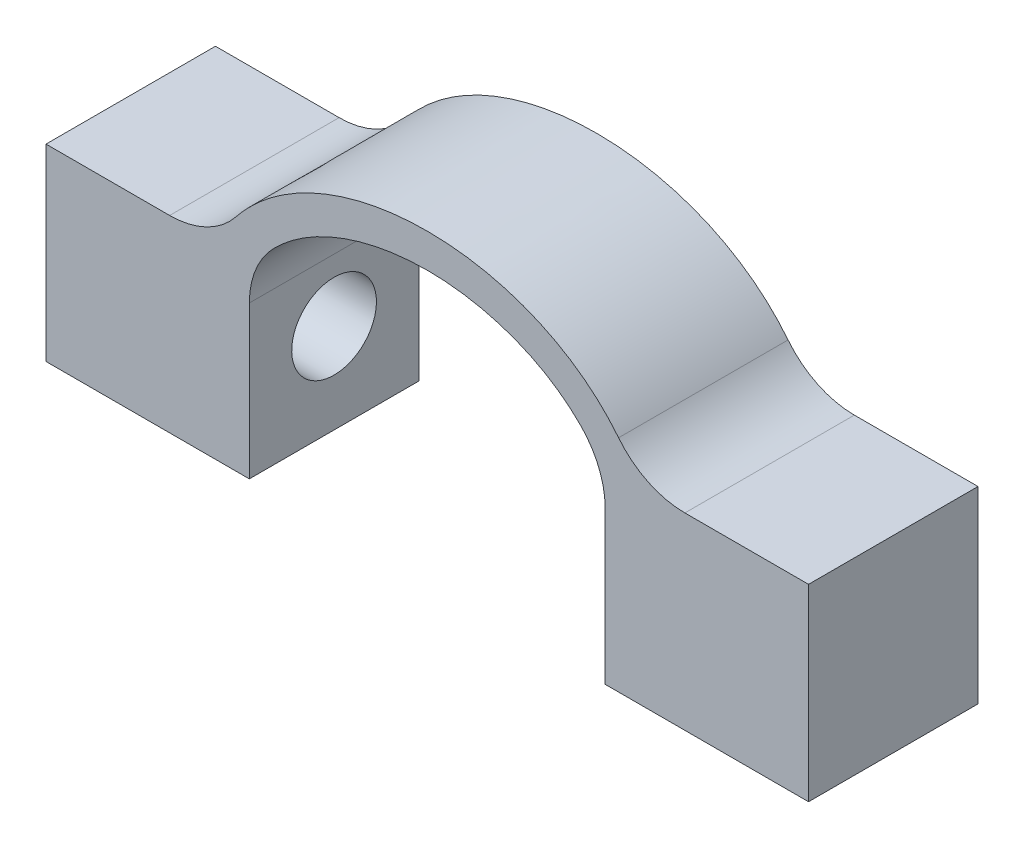
SolidWorks part; units mm, degrees
ref_plane "Front Plane" through (0, 0, 0) normal (0, 0, 1) x (1, 0, 0)
ref_plane "Top Plane" through (0, 0, 0) normal (0, 1, 0) x (1, 0, 0)
ref_plane "Right Plane" through (0, 0, 0) normal (1, 0, 0) x (0, 0, -1)
sketch "Sketch1" plane through (0, 0, 0) normal (0, 0, 1) x (1, 0, 0)
  line L4 (0, 0) -> (45, 0)
  line L5 (0, 0) -> (0, 11.1125)
  line L6 (0, 11.1125) -> (45, 11.1125) construction
  line L9 (15, 16.1125) -> (15, 11.1125) construction
  line L10 (30, 16.1125) -> (30, 11.1125) construction
  line L11 (0, 11.1125) -> (10, 11.1125)
  line L12 (35, 11.1125) -> (45, 11.1125)
  line L13 (45, 11.1125) -> (45, 0)
  spline S0 degree 3 poles (10, 11.1125) (14.5766, 20.182) (30.4234, 20.182) (35, 11.1125) knots 0 0 0 0 1 1 1 1
  dimension "D5" = 5
  dimension "D1" = 10
  dimension "D2" = 10
  dimension "D3" = 25
  dimension "D4" = 11.1125
  dimension "D6" = 5
  dimension "D7" = 5
extrude "Boss-Extrude1" add sketch "Sketch1" against normal blind 10
sketch "Sketch2" plane through (0, 0, 0) normal (0, 0, 1) x (1, 0, 0)
  line L0 (0, 0) -> (45, 0) construction
  line L2 (10, 11.1125) -> (10, 0) construction
  line L3 (10, 0) -> (35, 0) construction
  line L4 (35, 11.1125) -> (35, 0) construction
  line L5 (33, 10.6109) -> (33, 0)
  line L6 (12, 10.6109) -> (12, 0)
  spline S0 degree 3 poles (-1884.251, -531.3416) (2112.7694, 200.999) (-2067.7633, 201) (1929.2342, -531.3385) knots -3.992988 -3.992988 -3.992988 -3.992988 4.992976 4.992976 4.992976 4.992976 only from (35, 11.1125) to (10, 11.1125) construction
  spline S1 degree 3 poles (35, 11.1125) (30.4234, 20.182) (14.5766, 20.182) (10, 11.1125) knots 0 0 0 0 1 1 1 1 construction
  spline S2 degree 1 poles (33, 10.6109) (12, 10.6109) knots 0 0 1 1 construction
  spline S3 degree 3 poles (33, 10.6109) (32.5185, 11.4554) (31.2713, 12.9823) (27.9312, 15.2011) (22.5, 16.3903) (17.0688, 15.2011) (13.7287, 12.9823) (12.4815, 11.4554) (12, 10.6109) knots 0.018308 0.018308 0.018308 0.018308 0.138731 0.259154 0.5 0.740846 0.861269 0.981692 0.981692 0.981692 0.981692
  dimension "D1" = 2
extrude "Cut-Extrude2" cut sketch "Sketch2" against normal through all both and the other way through all
sketch "Sketch3" plane through (12, 0, 0) normal (1, 0, 0) x (0, 0, -1)
  line L0 (10, 10.6109) -> (0, 0) construction
  circle A0 centre (5, 5.3055) radius 2.5
  dimension "D1" = 5
extrude "Cut-Extrude3" cut sketch "Sketch3" against normal blind 6
sketch "Sketch4" plane through (6, 0, 0) normal (1, 0, 0) x (0, 0, -1)
  line L0 (2.5, 5.3055) -> (7.5, 5.3055) construction
  line L1 (5, 2.8055) -> (5, 7.8055) construction
  line L2 (5, 2.8055) -> (7.5, 2.8055) construction
  circle A0 centre (5, 5.3055) radius 2.5 construction
  circle A1 centre (5, 5.3055) radius 2
  dimension "D1" = 4
revolve "Cut-Revolve1" cut sketch "Sketch4" angle 90 about L2
sketch "Sketch5" plane through (0, 2.8055, 0) normal (0, 1, 0) x (1, 0, 0)
  circle A0 centre (3.5, 5) radius 2 construction
  circle A1 centre (3.5, 5) radius 2
extrude "Cut-Extrude4" cut sketch "Sketch5" against normal up to surface (2.8055 mm away) up to face at (6, 0, -5)
ref_plane "Plane1" through (22.5, 0, 0) normal (1, 0, 0) x (0, 0, -1)
mirror "Mirror1" about plane through (22.5, 0, 0) normal (1, 0, 0) of "Cut-Extrude4", "Cut-Revolve1", "Cut-Extrude3"
fillet "Fillet1" radius 5 4 edges at (10, 11.1125, -5) (35, 11.1125, -5) (33, 10.6109, -5) (12, 10.6109, -5)
